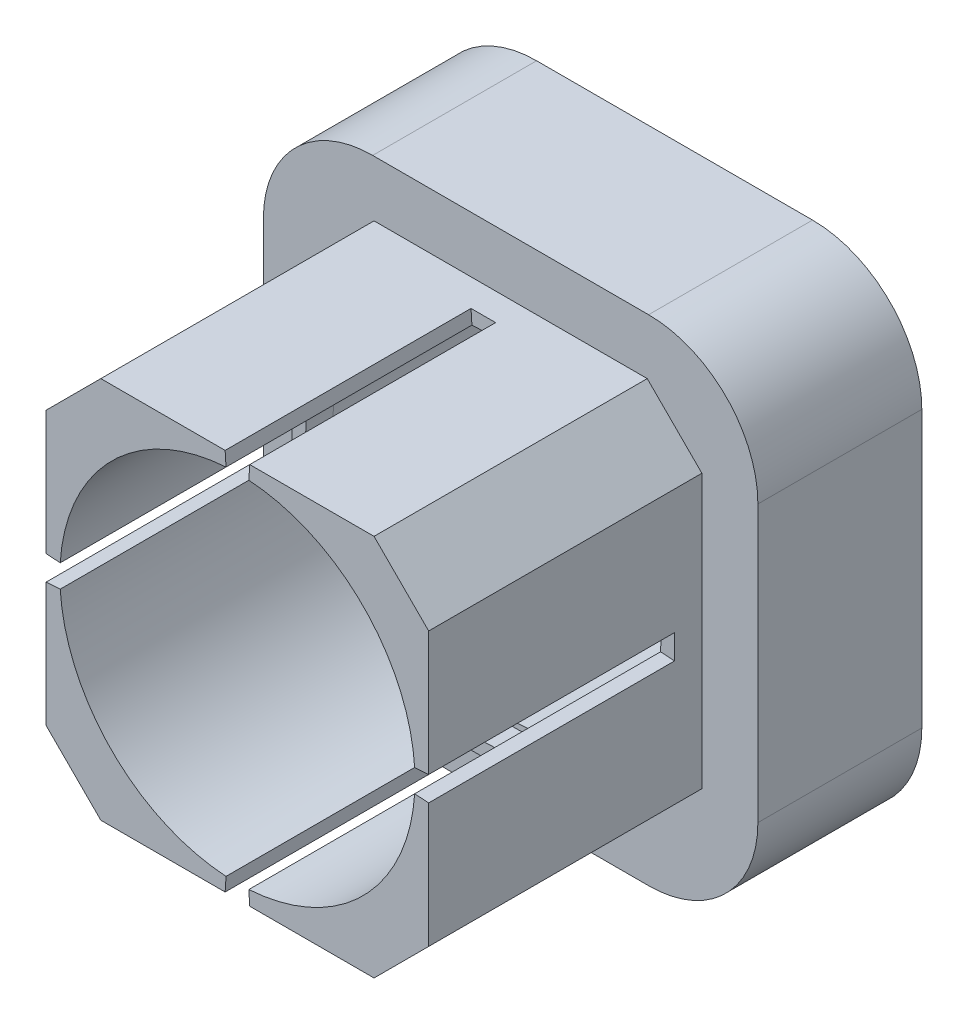
SolidWorks part; units mm, degrees
ref_plane "Front Plane" through (0, 0, 0) normal (0, 0, 1) x (1, 0, 0)
ref_plane "Top Plane" through (0, 0, 0) normal (0, 1, 0) x (1, 0, 0)
ref_plane "Right Plane" through (0, 0, 0) normal (1, 0, 0) x (0, 0, -1)
sketch "Sketch1" plane through (0, 0, 0) normal (0, 0, 1) x (1, 0, 0)
  line L0 (-5.05, 9.05) -> (5.05, 9.05)
  line L1 (9.05, -5.05) -> (9.05, 5.05)
  line L2 (0, 0) -> (0, 14.1446) construction
  line L3 (-9.05, -5.05) -> (-9.05, 5.05)
  line L4 (-12.732, 0) -> (15.0845, 0) construction
  line L5 (-5.05, -9.05) -> (5.05, -9.05)
  arc A4 (5.05, 9.05) -> (9.05, 5.05) centre (5.05, 5.05) cw
  arc A5 (9.05, -5.05) -> (5.05, -9.05) centre (5.05, -5.05) cw
  arc A6 (-5.05, -9.05) -> (-9.05, -5.05) centre (-5.05, -5.05) cw
  arc A7 (-9.05, 5.05) -> (-5.05, 9.05) centre (-5.05, 5.05) cw
  point P11 (9.05, 0)
  point P12 (0, 9.05)
  point P20 (0, -9.05)
  point P21 (-9.05, 0)
  dimension "D3" = 0
  dimension "D1" = 5.05
  dimension "D2" = 5.05
  dimension "D4" = 9.05
  dimension "D5" = 9.05
extrude "Boss-Extrude1" add sketch "Sketch1" along normal blind 6
sketch "Sketch3" plane through (0, 0, 6) normal (0, 0, 1) x (1, 0, 0)
  line L0 (-5, -7) -> (5, -7)
  line L1 (-7, -5) -> (-7, 5)
  line L2 (-5, 7) -> (5, 7)
  line L3 (7, -5) -> (7, 5)
  line L4 (-7, -7) -> (7, 7) construction
  line L5 (-7, 7) -> (7, -7) construction
  line L7 (-5, 7) -> (-7, 5)
  line L8 (-7, -5) -> (-5, -7)
  line L9 (5, -7) -> (7, -5)
  line L10 (5, 7) -> (7, 5)
  circle A6 centre (0, 0) radius 6.5
  point P3 (0, 0)
  dimension "D1" = 14
  dimension "D3" = 13
  dimension "D4" = 0
  dimension "D5" = 0
  dimension "D6" = 0
extrude "Boss-Extrude2" add sketch "Sketch3" along normal blind 10
sketch "Sketch11" plane through (0, 0, 16) normal (0, 0, 1) x (1, 0, 0)
  line L0 (0, 0) -> (7, 0.45)
  line L1 (7, -5) -> (7, 5) construction
  line L2 (7, 0.45) -> (7, -0.45)
  line L3 (7, -0.45) -> (0, 0)
  dimension "D1" = 0.45
  dimension "D2" = 0.45
extrude "Cut-Extrude7" cut sketch "Sketch11" against normal blind 9
pattern_circular "CirPattern1" count 4 over 360 about axis through (0, 0, 16) along (0, 0, -1) of "Cut-Extrude7"
sketch "Sketch12" plane through (0, 0, 6) normal (0, 0, 1) x (1, 0, 0)
  line L0 (0, 0) -> (0, 14.1446) construction
  circle A0 centre (0, 0.1925) radius 6.5
  dimension "D1" = 13
extrude "Cut-Extrude8" cut sketch "Sketch12" against normal blind 30
